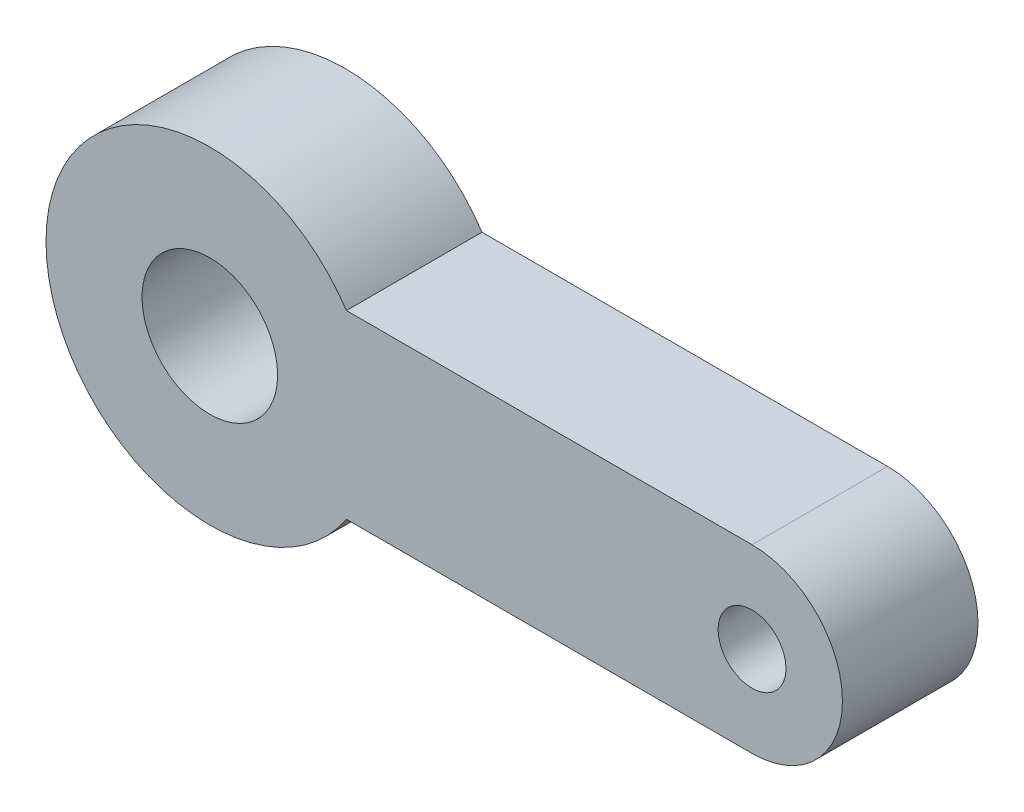
SolidWorks part; units mm, degrees
ref_plane "前视基准面" through (0, 0, 0) normal (0, 0, 1) x (1, 0, 0)
ref_plane "上视基准面" through (0, 0, 0) normal (0, 1, 0) x (1, 0, 0)
ref_plane "右视基准面" through (0, 0, 0) normal (1, 0, 0) x (0, 0, -1)
sketch "草图1" plane through (0, 0, 0) normal (0, 0, 1) x (1, 0, 0)
  line L0 (0, 0) -> (50000, 0) construction
  line L1 (0, 0) -> (0, 50000) construction
  line L2 (13.625, 4) -> (-4.3283, 4)
  line L3 (-17.625, 7.25) -> (17.625, 7.25)
  line L4 (-17.625, 7.25) -> (-17.625, -7.25)
  line L5 (-17.625, -7.25) -> (17.625, -7.25)
  line L6 (17.625, 7.25) -> (17.625, -7.25)
  line L7 (-4.3283, -4) -> (13.625, -4)
  circle A0 centre (-10.375, 0) radius 7.25
  circle A1 centre (13.625, 0) radius 4
  dimension "D3" = 7.25
  dimension "D4" = 4
  dimension "D1" = 35.25
  dimension "D2" = 14.5
extrude "凸台-拉伸1" add sketch "草图1" along normal blind 6 contours A0 | A1 L2 A0 L7 | A1
sketch "草图2" plane through (0, 0, 6) normal (0, 0, 1) x (1, 0, 0)
  line L0 (-10.375, 7.25) -> (-10.375, 50007.25) construction
  line L1 (0, 0) -> (50000, 0) construction
  circle A0 centre (13.625, 0) radius 1.5
  circle A2 centre (-10.375, 0) radius 3
extrude "切除-拉伸1" cut sketch "草图2" against normal blind 6 contours A2 | A0
